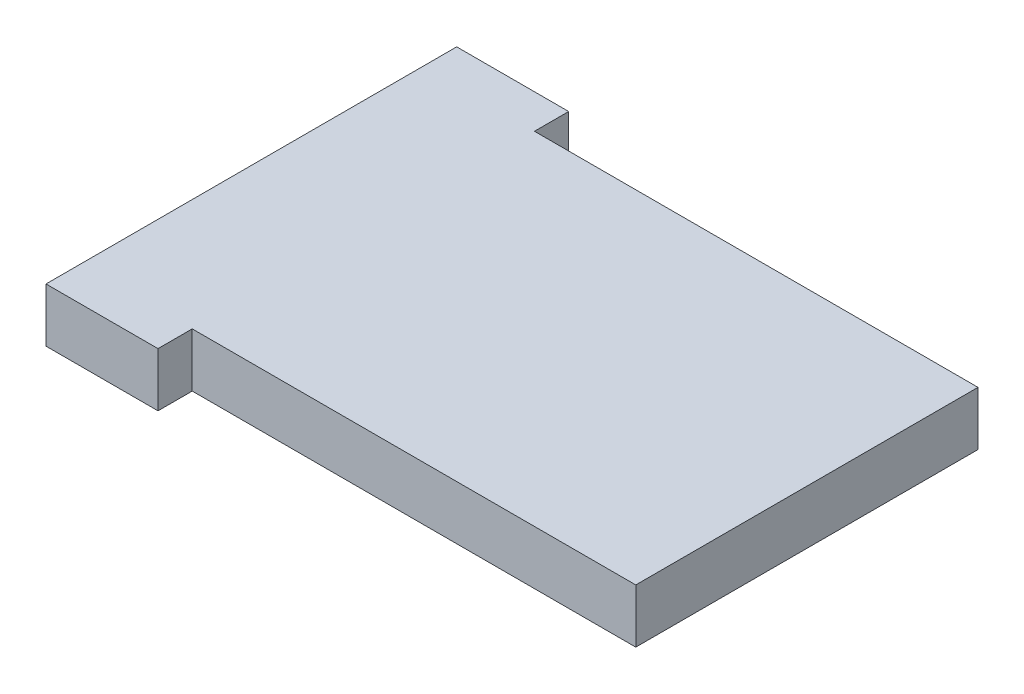
SolidWorks part; units mm, degrees
ref_plane "Front Plane" through (0, 0, 0) normal (0, 0, 1) x (1, 0, 0)
ref_plane "Top Plane" through (0, 0, 0) normal (0, 1, 0) x (1, 0, 0)
ref_plane "Right Plane" through (0, 0, 0) normal (1, 0, 0) x (0, 0, -1)
sketch "Sketch1" plane through (0, 0, 0) normal (0, 1, 0) x (1, 0, 0)
  line L0 (0, 19.05) -> (0, -19.05)
  line L1 (0, -19.05) -> (10.3911, -19.05)
  line L2 (10.3911, -19.05) -> (10.3911, -15.875)
  line L3 (10.3911, -15.875) -> (51.5386, -15.875)
  line L4 (51.5386, -15.875) -> (51.5386, 15.875)
  line L5 (51.5386, 15.875) -> (10.3911, 15.875)
  line L6 (10.3911, 15.875) -> (10.3911, 19.05)
  line L7 (10.3911, 19.05) -> (0, 19.05)
  line L8 (10.3911, 15.875) -> (10.3911, -15.875) construction
  line L9 (0, 0) -> (51.5386, 0) construction
  dimension "D1" = 38.1
  dimension "D2" = 31.75
extrude "Boss-Extrude1" add sketch "Sketch1" along normal blind 5
